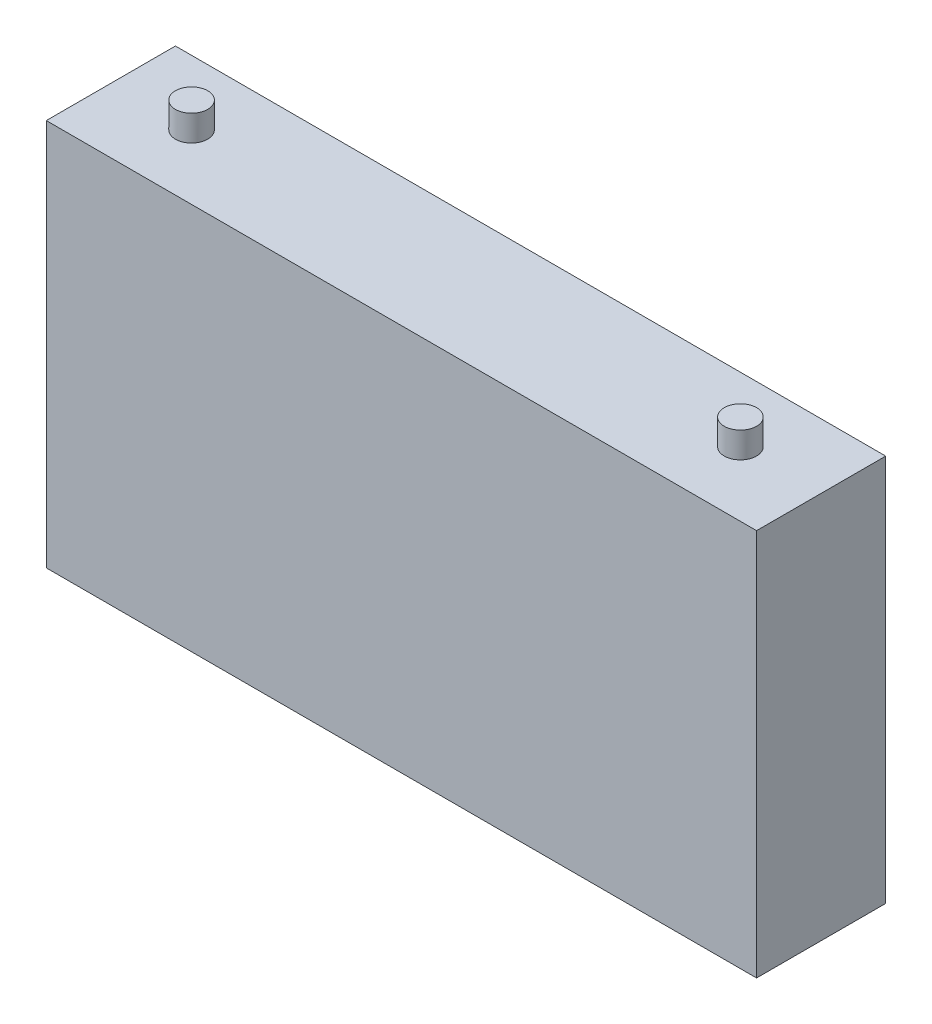
SolidWorks part; units mm, degrees
material "ABS"
ref_plane "正面" through (0, 0, 0) normal (0, 0, 1) x (1, 0, 0)
ref_plane "平面" through (0, 0, 0) normal (0, 1, 0) x (1, 0, 0)
ref_plane "右側面" through (0, 0, 0) normal (1, 0, 0) x (0, 0, -1)
sketch "ｽｹｯﾁ1" plane through (0, 0, 0) normal (0, 0, 1) x (1, 0, 0)
  line L1 (-110, -60) -> (110, -60)
  line L2 (-110, -60) -> (-110, 60)
  line L3 (-110, 60) -> (110, 60)
  line L4 (110, -60) -> (110, 60)
  line L5 (-110, -60) -> (110, 60) construction
  line L6 (-110, 60) -> (110, -60) construction
  point P0 (0, 0)
extrude "ﾎﾞｽ - 押し出し1" add sketch "ｽｹｯﾁ1" along normal mid plane 40
sketch "ｽｹｯﾁ2" plane through (0, 0, 0) normal (0, 1, 0) x (1, 0, 0)
  circle A0 centre (85, 0) radius 5
  circle A1 centre (-85, 0) radius 5
extrude "ﾎﾞｽ - 押し出し2" add sketch "ｽｹｯﾁ2" along normal blind 8 from offset 60
sketch "ｽｹｯﾁ3" plane through (0, 0, 0) normal (0, 1, 0) x (1, 0, 0)
  circle A0 centre (85, 0) radius 5
  circle A1 centre (-85, 0) radius 5
extrude "ﾎﾞｽ - 押し出し3" add sketch "ｽｹｯﾁ3" against normal blind 8 from offset 60
